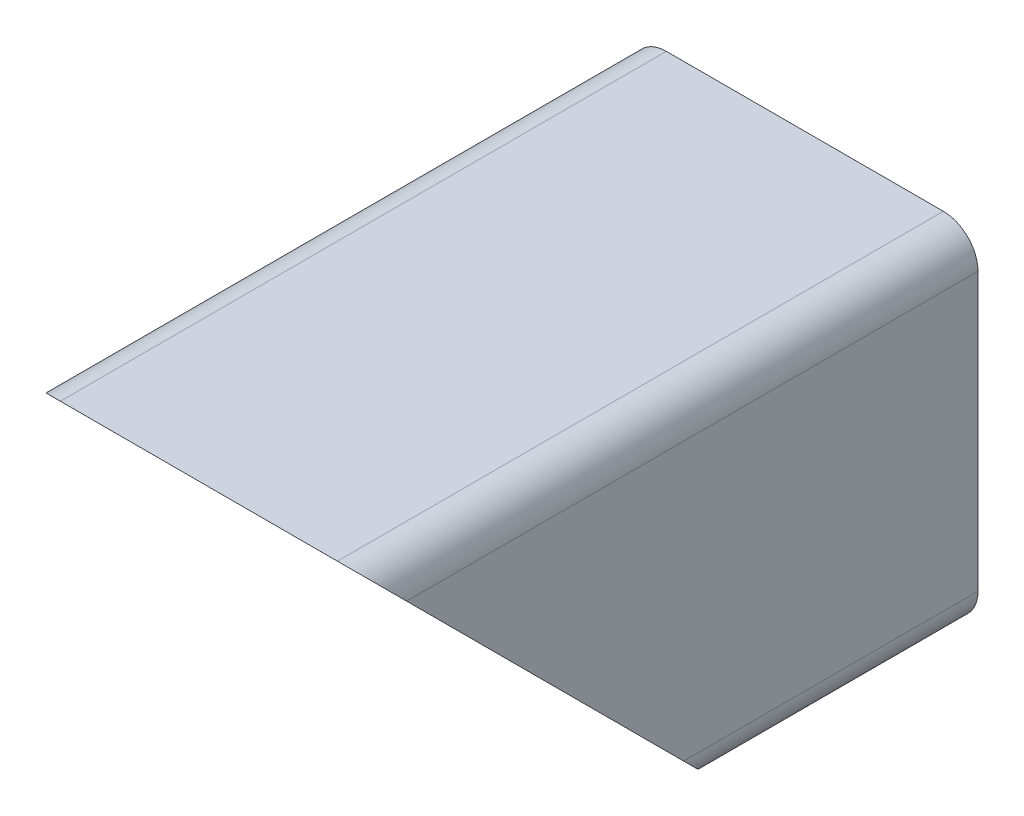
SolidWorks part; units mm, degrees
material "1.4305 (X8CrNiS18-9)"
ref_plane "Ön Düzlem" through (0, 0, 0) normal (0, 0, 1) x (1, 0, 0)
ref_plane "Üst Düzlem" through (0, 0, 0) normal (0, 1, 0) x (1, 0, 0)
ref_plane "Sağ Düzlem" through (0, 0, 0) normal (1, 0, 0) x (0, 0, -1)
sketch "Çizim1" plane through (0, 0, 0) normal (0, 0, 1) x (1, 0, 0)
  line L0 (-18, 16) -> (-18, -16)
  line L1 (-16, 20) -> (16, 20)
  line L2 (-20, 16) -> (-20, -16)
  line L3 (-16, -20) -> (16, -20)
  line L4 (20, 16) -> (20, -16)
  line L5 (-20, 20) -> (20, -20) construction
  line L6 (-20, -20) -> (20, 20) construction
  line L7 (-16, -18) -> (16, -18)
  line L8 (18, 16) -> (18, -16)
  line L9 (-16, 18) -> (16, 18)
  arc A0 (20, -16) -> (16, -20) centre (16, -16) cw
  arc A1 (16, 20) -> (20, 16) centre (16, 16) cw
  arc A2 (-16, 20) -> (-20, 16) centre (-16, 16) ccw
  arc A3 (-20, -16) -> (-16, -20) centre (-16, -16) ccw
  arc A4 (-18, -16) -> (-16, -18) centre (-16, -16) ccw
  arc A5 (18, -16) -> (16, -18) centre (16, -16) cw
  arc A6 (16, 18) -> (18, 16) centre (16, 16) cw
  arc A7 (-16, 18) -> (-18, 16) centre (-16, 16) ccw
  point P0 (0, 0)
  dimension "D3" = 4
  dimension "D1" = 40
  dimension "D2" = 40
  dimension "D4" = 2
extrude "Yükseklik-Ekstrüzyon1" add sketch "Çizim1" along normal blind 70
sketch "Çizim2" plane through (0, 0, 0) normal (0, 0, -1) x (-1, 0, 0)
  line L0 (-18.8284, 18.8284) -> (18.8284, -18.8284) construction
  arc A0 (-16, 20) -> (-20, 16) centre (-16, 16) ccw construction
  arc A1 (16, -20) -> (20, -16) centre (16, -16) ccw construction
sketch "Çizim3" plane through (0, 0, 0) normal (1, 0, 0) x (0, 0, -1)
  line L0 (-70, 20) -> (-30, -20)
  line L1 (-70, -20) -> (0, -20) construction
  line L2 (-30, -20) -> (-70, -20)
  line L3 (-70, -20) -> (-70, 20)
  dimension "D1" = 45
extrude "Kes-Ekstrüzyon1" cut sketch "Çizim3" against normal blind 43 and the other way blind 41
